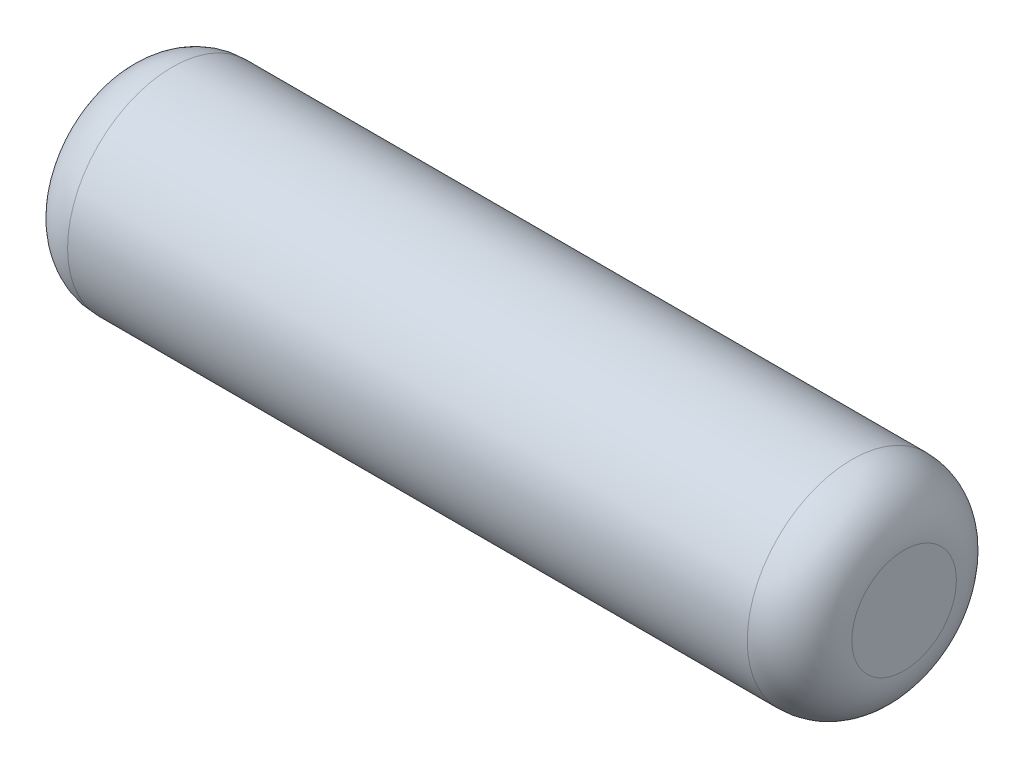
SolidWorks part; units mm, degrees
ref_plane "前视基准面" through (0, 0, 0) normal (0, 0, 1) x (1, 0, 0)
ref_plane "上视基准面" through (0, 0, 0) normal (0, 1, 0) x (1, 0, 0)
ref_plane "右视基准面" through (0, 0, 0) normal (1, 0, 0) x (0, 0, -1)
sketch "草图1" plane through (0, 0, 0) normal (1, 0, 0) x (0, 0, -1)
  circle A0 centre (0, 0) radius 2
extrude "凸台-拉伸1" add sketch "草图1" along normal mid plane 15
fillet "圆角1" radius 1 2 edges at (-7.5, 0, -2) (7.5, 0, -2)
